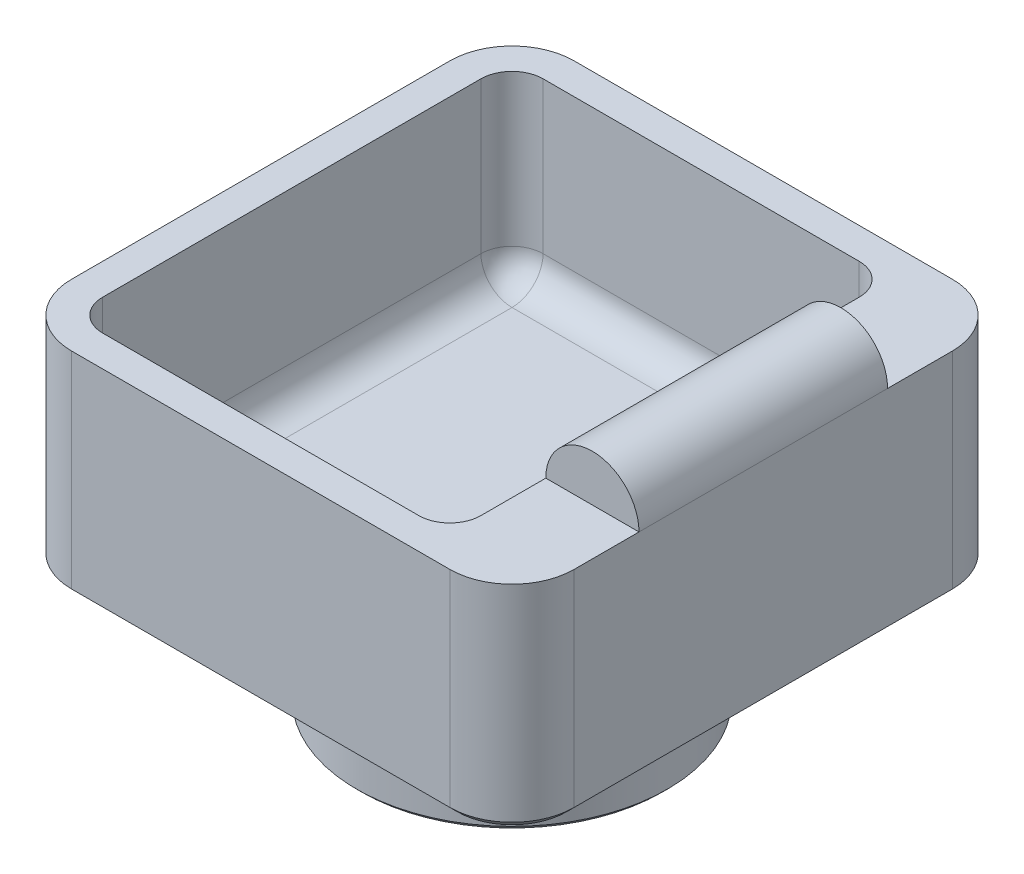
SolidWorks part; units mm, degrees
material "PLA"
ref_plane "Front Plane" through (0, 0, 0) normal (0, 0, 1) x (1, 0, 0)
ref_plane "Top Plane" through (0, 0, 0) normal (0, 1, 0) x (1, 0, 0)
ref_plane "Right Plane" through (0, 0, 0) normal (1, 0, 0) x (0, 0, -1)
sketch "Sketch1" plane through (0, 0, 0) normal (0, 1, 0) x (1, 0, 0)
  line L4 (25.6779, 25.6779) -> (25.6779, -25.6779)
  line L5 (25.6779, -25.6779) -> (-25.6779, -25.6779)
  line L6 (-25.6779, -25.6779) -> (-25.6779, 25.6779)
  line L7 (-25.6779, 25.6779) -> (25.6779, 25.6779)
  circle A0 centre (0, 0) radius 36.3141 construction
  dimension "D1" = 72.6281
extrude "Boss-Extrude1" add sketch "Sketch1" along normal blind 21.8281
fillet "Fillet1" radius 6.35 4 edges at (25.6779, 10.9141, -25.6779) (25.6779, 10.9141, 25.6779) (-25.6779, 10.9141, 25.6779) (-25.6779, 10.9141, -25.6779)
shell "Shell1" thickness 3.175
sketch "Sketch2" plane through (0, 0, 0) normal (0, -1, 0) x (1, 0, 0)
  circle A0 centre (0, 0) radius 15.875
  dimension "D1" = 31.75
extrude "Boss-Extrude2" add sketch "Sketch2" along normal blind 12.7
sketch "Sketch3" plane through (0, 3.175, 0) normal (0, 1, 0) x (1, 0, 0)
  line L0 (16.1529, 22.5029) -> (16.1529, -22.5029)
  line L1 (19.3279, 22.5029) -> (-19.3279, 22.5029) construction
  line L2 (-19.3279, -22.5029) -> (19.3279, -22.5029) construction
  line L3 (16.1529, -22.5029) -> (22.5029, -22.5029)
  line L4 (22.5029, -22.5029) -> (22.5029, 22.5029)
  line L5 (22.5029, 22.5029) -> (16.1529, 22.5029)
  line L6 (25.6779, -19.3279) -> (25.6779, 19.3279) construction
  line L7 (22.5029, -19.3279) -> (22.5029, 19.3279) construction
  dimension "D1" = 9.525
extrude "Boss-Extrude3" add sketch "Sketch3" along normal up to surface (18.6531 mm away) up to face at (0, 21.8281, 0)
ref_plane "Plane2" through (0, 0, 0) normal (0, 0, 1) x (1, 0, 0)
sketch "Sketch4" plane through (0, 0, 0) normal (0, 0, 1) x (1, 0, 0)
  line L0 (-19.3279, 21.8281) -> (19.3279, 21.8281) construction
  line L1 (25.6779, 21.8281) -> (25.6779, 0) construction
  circle A0 centre (20.9154, 21.8281) radius 4.7625
  dimension "D1" = 9.525
extrude "Boss-Extrude4" add sketch "Sketch4" along normal mid plane 25.4
sketch "Sketch5" plane through (0, 0, 12.7) normal (0, 0, 1) x (1, 0, 0)
  line L0 (20.9154, 26.5906) -> (20.9154, 21.8281)
  arc A0 (25.6779, 21.8281) -> (16.1529, 21.8281) centre (20.9154, 21.8281) ccw construction
  circle A1 centre (20.9154, 24.2094) radius 1.5875
  point P8 (20.9154, 24.2094)
  dimension "D1" = 3.175
extrude "Cut-Extrude1" cut sketch "Sketch5" against normal blind 25.4 contours L0 A1 | L0 A1
sketch "Sketch6" plane through (0, 0, 12.7) normal (0, 0, 1) x (1, 0, 0)
  circle A0 centre (20.9154, 24.2094) radius 1.9668
extrude "Boss-Extrude5" add sketch "Sketch6" against normal blind 0.7937
fillet "Fillet2" radius 3.175 2 edges at (16.1529, 12.5016, 22.5029) (16.1529, 12.5016, -22.5029)
fillet "Fillet3" radius 3.175 8 edges at (-21.573, 3.175, 21.573) (-22.5029, 3.175, 0) (-21.573, 3.175, -21.573) (-3.175, 3.175, -22.5029) (15.223, 3.175, -21.573) (16.1529, 3.175, 0) (15.223, 3.175, 21.573) (-3.175, 3.175, 22.5029)
sketch "Sketch8" plane through (0, -12.7, 0) normal (0, -1, 0) x (1, 0, 0)
  circle A2 centre (0, 0) radius 13.335
  circle A3 centre (0, 0) radius 13.335
  dimension "D1" = 2.54
extrude "Cut-Extrude2" cut sketch "Sketch8" against normal up to surface (12.7 mm away) up to face at (0, 0, -15.875)
sketch "Sketch9" plane through (0, 0, 0) normal (0, 1, 0) x (1, 0, 0)
  line L0 (-12.0055, 0) -> (12.0055, 0) construction
  line L1 (-15.875, 0) -> (-13.335, 0) construction
  circle A0 centre (-14.605, 0) radius 0.1
  circle A1 centre (0, 0) radius 15.875 construction
  circle A2 centre (0, 0) radius 13.335 construction
  dimension "D1" = 0.2
extrude "Cut-Extrude3" cut sketch "Sketch9" against normal blind 6.35 and the other way blind 2.54
pattern_circular "CirPattern1" count 4 over 360 about axis through (0, 0, 0) along (0, 1, 0) of "Cut-Extrude3"
other "SurfaceCut1" [suppressed]
chamfer "Chamfer4" distance 0.762 angle 45 8 edges at (0, 0, 25.6779) (23.818, 0, 23.818) (-23.818, 0, 23.818) (25.6779, 0, 0) (-25.6779, 0, 0) (23.818, 0, -23.818) (-23.818, 0, -23.818) (0, 0, -25.6779)
chamfer "Chamfer5" distance 0.508 angle 45 2 edges at (0, -12.7, -15.875) (0, -12.7, -13.335)
